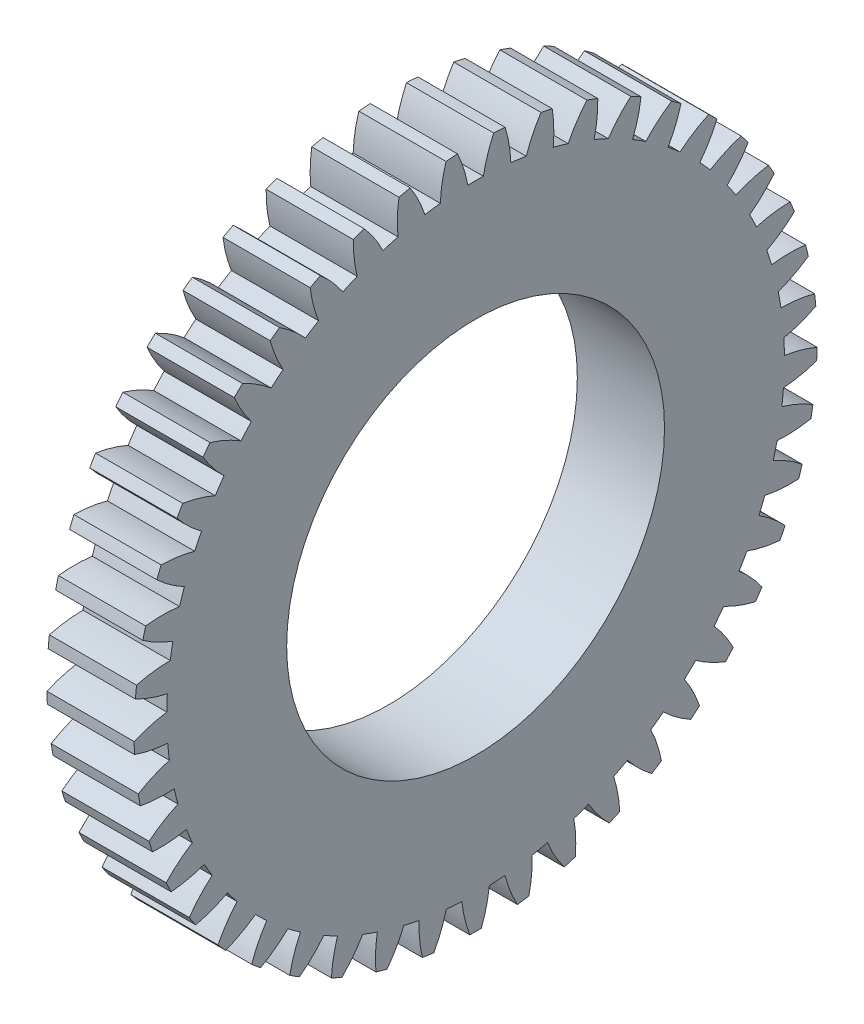
SolidWorks part; units mm, degrees
material "ABS"
ref_plane "Plane1" through (0, 0, 0) normal (0, 0, 1) x (1, 0, 0)
ref_plane "Plane2" through (0, 0, 0) normal (0, 1, 0) x (1, 0, 0)
ref_plane "Plane3" through (0, 0, 0) normal (1, 0, 0) x (0, 0, -1)
other "Configuration Table"
sketch "HoldingSke" plane through (0, 0, 0) normal (0, 1, 0) x (1, 0, 0)
  line L0 (0, 0) -> (0.7071, -0.7071)
  line L1 (-15, 0) -> (100, 0) construction
  line L2 (0, 0) -> (-2.1039, 2.3779)
  line L3 (0, 0) -> (-11.863, 4.5341)
  line L4 (0, 0) -> (6.1066, 6.1066)
  line L5 (0, 0) -> (-46.8476, -17.4728)
  line L6 (0, 0) -> (-4.9738, -3.3558)
  line L7 (-2.1039, 2.3779) -> (8.6586, 51.2059)
  line L8 (-76.2, 54.61) -> (-72.9, 54.61)
  line L9 (-67.7845, 28.3722) -> (-49.3413, 33.142)
  line L10 (-76.2, 71.12) -> (104.1128, 71.12)
  line L11 (0, 0) -> (-6, 0)
  line L12 (-76.2, 101.6) -> (-76.162, 101.6)
  line L13 (24.9733, 27.94) -> (52.9518, 28.4284)
  line L14 (24.9733, 27.94) -> (24.9743, 27.94)
  line L15 (24.9733, 27.94) -> (100.4006, 29.5858)
  line L16 (-63.627, -1) -> (-12.827, -1)
  circle A0 centre (0, 0) radius 13
  circle A1 centre (0, 0) radius 21.249
  circle A2 centre (0, 0) radius 37.5
  circle A3 centre (0, 0) radius 13
  dimension "MHD" = 42.498
  dimension "Hub_dia" = 75
  dimension "Bore" = 26
  dimension "MBD" = 26
  dimension "Num_teeth" = 45
  dimension "Pitch" = 1
  dimension "Overall_len" = 50
  dimension "Show_teeth" = 45
  dimension "Thickness" = 6
  dimension "OAL" = 50.0001
  dimension "T_dim" = 3.3
  dimension "Ap" = 14.5
  dimension "H" = 19.05
  dimension "Pitch_radius" = 180.3128
  dimension "Width" = 6
  dimension "Backlash" = 0.038
  dimension "Addendum_fac" = 1
  dimension "Dedendum_fac" = 1.25
  dimension "Clearance_fac" = 0.25
  dimension "Dedendum_add" = 0.001
  dimension "Module" = 1
sketch "BasProSke" plane through (0, 0, 0) normal (0, 1, 0) x (1, 0, 0)
  line L0 (-10, 0) -> (60, 0) construction
  line L1 (0, 0) -> (0, 23.5)
  line L2 (0, 0) -> (6, 0)
  line L3 (6, 0) -> (6, 23.5)
  line L4 (6, 23.5) -> (0, 23.5)
  dimension "Thickness" = 6
  dimension "Diameter" = 47
revolve "Base-Revolve" add sketch "BasProSke" angle 360 about L0
sketch "TooCutSke" plane through (0, 0, 0) normal (1, 0, 0) x (0, 0, -1)
  line L1 (0, 0) -> (0, 107) construction
  line L2 (0, 0) -> (-0.8517, 22.4839) construction
  line L3 (0, 0) -> (-3.1374, 44.8675) construction
  line L4 (-0.8517, 22.4839) -> (-1.5687, 22.4337) construction
  arc A0 (0.5364, 21.2422) -> (-0.5364, 21.2422) centre (0, 0) ccw
  arc A1 (1.2547, 23.4919) -> (-1.2547, 23.4919) centre (0, 0) ccw
  circle A2 centre (0, 0) radius 22.5 construction
  circle A3 centre (0, 0) radius 21.7833 construction
  arc A4 (-0.5364, 21.2422) -> (-1.2547, 23.4919) centre (-9.395, 19.6532) ccw
  arc A5 (1.2547, 23.4919) -> (0.5364, 21.2422) centre (9.395, 19.6532) ccw
  dimension "Root_dia" = 42.498
  dimension "Overcut_dia" = 47.0508
  dimension "Pitch_dia" = 45
  dimension "Base_dia" = 43.5666
  dimension "Flank_rad" = 9
  dimension "Half_ang" = 4
  dimension "Half_CT" = 0.7187
extrude "ToothCut" cut sketch "TooCutSke" along normal through all
fillet "Breaks" [suppressed] radius 0.02
fillet "RootFillets" [suppressed] radius 0.251
pattern_circular "TeethCuts" count 45 every 8 about axis through (-10, 0, 0) along (1, 0, 0) of "ToothCut", "RootFillets", "Breaks"
sketch "HubNeaOneSke" plane through (0, 0, 0) normal (-1, 0, 0) x (0, 0, 1)
  circle A0 centre (0, 0) radius 21.249
  dimension "Diameter" = 42.498
extrude "HubNearOne" [suppressed] add sketch "HubNeaOneSke" along normal blind 44.0001
sketch "HubNeaBotSke" plane through (0, 0, 0) normal (-1, 0, 0) x (0, 0, 1)
  circle A0 centre (0, 0) radius 21.249
  dimension "Diameter" = 42.498
extrude "HubNearBoth" [suppressed] add sketch "HubNeaBotSke" along normal blind 22
ref_plane "FarPln" through (6, 0, 0) normal (1, 0, 0) x (0, 0, -1)
sketch "HubFarSke" plane through (6, 0, 0) normal (1, 0, 0) x (0, 0, -1)
  circle A0 centre (0, 0) radius 21.249
  dimension "Diameter" = 42.498
extrude "HubFar" [suppressed] add sketch "HubFarSke" along normal blind 22
sketch "BorSke" plane through (0, 0, 0) normal (1, 0, 0) x (0, 0, -1)
  circle A0 centre (0, 0) radius 13
  dimension "Diameter" = 26
extrude "Bore" cut sketch "BorSke" along normal mid plane 100.0001
sketch "KeySke" plane through (0, 0, 0) normal (1, 0, 0) x (0, 0, -1)
  line L0 (-4, 0) -> (-4, 16.3)
  line L1 (-4, 16.3) -> (4, 16.3)
  line L2 (4, 16.3) -> (4, 0)
  line L3 (0, 0) -> (0, 34) construction
  line L4 (-4, 0) -> (4, 0)
  dimension "Offset" = 16.3
  dimension "Width" = 8
extrude "Keyway" [suppressed] cut sketch "KeySke" along normal mid plane 100.0001
pattern_circular "Keyway2" [suppressed] count 2 every 90 about axis through (-10, 0, 0) along (1, 0, 0)
equation "' \"Module@HoldingSke\" = 6.35"
equation "' \"Num_teeth@HoldingSke\" = 12"
equation "' \"Ap@HoldingSke\" =  20"
equation "' \"Ap@HoldingSke\" = 20"
equation "' \"Width@HoldingSke\" = 0.5 * 25.4"
equation "' \"Hub_dia@HoldingSke\"= 1 * 25.4"
equation "' \"Hub_dia@HoldingSke\" = 1 * 25.4"
equation "' \"Overall_len@HoldingSke\" = 1.0 * 25.4"
equation "' \"Bore@HoldingSke\" = 0.75 * 25.4"
equation "' \"T_dim@HoldingSke\" = 0.1 * 25.4"
equation "' \"Width@KeySke\" = 0.25 * 25.4"
equation "' \"Show_teeth@HoldingSke\" = 13"
equation "' \"Backlash@HoldingSke\" = 0.009 * 25.4"
equation "' \"Addendum_fac@HoldingSke\" = 1.0"
equation "' \"Dedendum_fac@HoldingSke\" = 1.25"
equation "' \"Dedendum_add@HoldingSke\" = 0.00005 * 25.4"
equation "' \"Clearance_fac@HoldingSke\" = 0.25"
equation "\"Pitch@HoldingSke\" = 1 / \"Module@HoldingSke\""
equation "\"Overcut_dia@TooCutSke\" = (\"Num_teeth@HoldingSke\" + 2 * \"Addendum_fac@HoldingSke\") / \"Pitch@HoldingSke\" + 0.002 * 25.4"
equation "\"Pitch_dia@TooCutSke\" = \"Num_teeth@HoldingSke\" / \"Pitch@HoldingSke\""
equation "\"Base_dia@TooCutSke\" = \"Num_teeth@HoldingSke\" / \"Pitch@HoldingSke\" * cos((\"Ap@HoldingSke\"  * 3.14159265 / 180))"
equation "\"Root_dia@TooCutSke\" = (\"Num_teeth@HoldingSke\" + 2) / \"Pitch@HoldingSke\" - 2 * (\"Addendum_fac@HoldingSke\" + \"Dedendum_fac@HoldingSke\") / \"Pitch@HoldingSke\" - \"Dedendum_add@HoldingSke\" * 2"
equation "\"Half_ang@TooCutSke\" = 180 / \"Num_teeth@HoldingSke\""
equation "\"Half_CT@TooCutSke\" = \"Num_teeth@HoldingSke\" / \"Pitch@HoldingSke\" * sin((3.14159265 / 2 / \"Num_teeth@HoldingSke\")) / 2 - 7 * \"Backlash@HoldingSke\" / 4"
equation "\"Flank_rad@TooCutSke\" = \"Num_teeth@HoldingSke\" / \"Pitch@HoldingSke\" / 5"
equation "\"Radius@RootFillets\" = \"Clearance_fac@HoldingSke\" / \"Pitch@HoldingSke\" + \"Dedendum_add@HoldingSke\""
equation "\"Break_rad@Breaks\" = 0.02 / \"Pitch@HoldingSke\""
equation "\"Thickness@HoldingSke\" = \"Width@HoldingSke\""
equation "\"OAL@HoldingSke\" = \"Thickness@HoldingSke\""
equation "\"MHD@HoldingSke\" = (\"Num_teeth@HoldingSke\" + 2) / \"Pitch@HoldingSke\" - 2 * (\"Addendum_fac@HoldingSke\" + \"Dedendum_fac@HoldingSke\")  / \"Pitch@HoldingSke\" - \"Dedendum_add@HoldingSke\" * 2"
equation "\"MBD@HoldingSke\" = (\"Num_teeth@HoldingSke\" + 2) / \"Pitch@HoldingSke\" - 2 * (\"Addendum_fac@HoldingSke\" + \"Dedendum_fac@HoldingSke\")  / \"Pitch@HoldingSke\" - \"Dedendum_add@HoldingSke\" * 2 - 0.002 * 25.4"
equation "\"MHD@HoldingSke\" = ((sgn( \"MHD@HoldingSke\" - \"Hub_dia@HoldingSke\" )-1)*( \"MHD@HoldingSke\" - \"Hub_dia@HoldingSke\" ))/-2+ \"Hub_dia@HoldingSke\""
equation "\"MBD@HoldingSke\" = ((sgn( \"MBD@HoldingSke\" - \"Bore@HoldingSke\" )-1)*( \"MBD@HoldingSke\" - \"Bore@HoldingSke\" ))/-2+ \"Bore@HoldingSke\""
equation "\"OAL@HoldingSke\" = ((sgn( \"OAL@HoldingSke\" - \"Overall_len@HoldingSke\" )+1)*( \"OAL@HoldingSke\" - \"Overall_len@HoldingSke\" ))/2 + \"Overall_len@HoldingSke\" + 0.000002 * 25.4"
equation "\"Num_teeth@TeethCuts\" = int( \"Show_teeth@HoldingSke\" ) + 1"
equation "\"Num_teeth@TeethCuts\" = ((sgn( \"Num_teeth@TeethCuts\" - \"Num_teeth@HoldingSke\" )-1)*( \"Num_teeth@TeethCuts\" - \"Num_teeth@HoldingSke\" ))/-2+ \"Num_teeth@HoldingSke\""
equation "\"Num_teeth@TeethCuts\" = ((sgn( \"Num_teeth@TeethCuts\" - 2.0)+1)*( \"Num_teeth@TeethCuts\" - 2.0))/2 +2.0"
equation "\"Angle@TeethCuts\" = 360.0 / \"Num_teeth@HoldingSke\""
equation "\"Diameter@BasProSke\" = (\"Num_teeth@HoldingSke\" + 2 * \"Addendum_fac@HoldingSke\") / \"Pitch@HoldingSke\""
equation "\"Thickness@BasProSke\"  = \"Thickness@HoldingSke\""
equation "' \"Fillet_rad@BasProSke\" =  \"Thickness@HoldingSke\" * 0.05"
equation "' \"Fillet_rad@BasProSke\" = \"Thickness@HoldingSke\" * 0.05"
equation "\"MHD@HoldingSke\" = ((sgn( \"MHD@HoldingSke\" - \"Root_dia@TooCutSke\" )-1)*( \"MHD@HoldingSke\" - \"Root_dia@TooCutSke\" ))/-2+ \"Root_dia@TooCutSke\""
equation "\"Diameter@HubNeaOneSke\" = \"MHD@HoldingSke\""
equation "\"Length@HubNearOne\" = \"OAL@HoldingSke\" - \"Thickness@BasProSke\""
equation "\"Diameter@HubNeaBotSke\" = \"MHD@HoldingSke\""
equation "\"Length@HubNearBoth\" = ( \"OAL@HoldingSke\" - \"Thickness@BasProSke\" ) / 2.0"
equation "\"Thickness@FarPln\" = \"Thickness@BasProSke\""
equation "\"Diameter@HubFarSke\" = \"MHD@HoldingSke\""
equation "\"Length@HubFar\" = ( \"OAL@HoldingSke\" - \"Thickness@BasProSke\" ) / 2.0"
equation "\"Diameter@BorSke\" = \"MBD@HoldingSke\""
equation "\"D1@Bore\" = \"OAL@HoldingSke\" * 2.0"
equation "\"D1@Keyway\" = \"OAL@HoldingSke\" * 2.0"
equation "\"Offset@KeySke\" = \"T_dim@HoldingSke\" + \"MBD@HoldingSke\" / 2.0"
